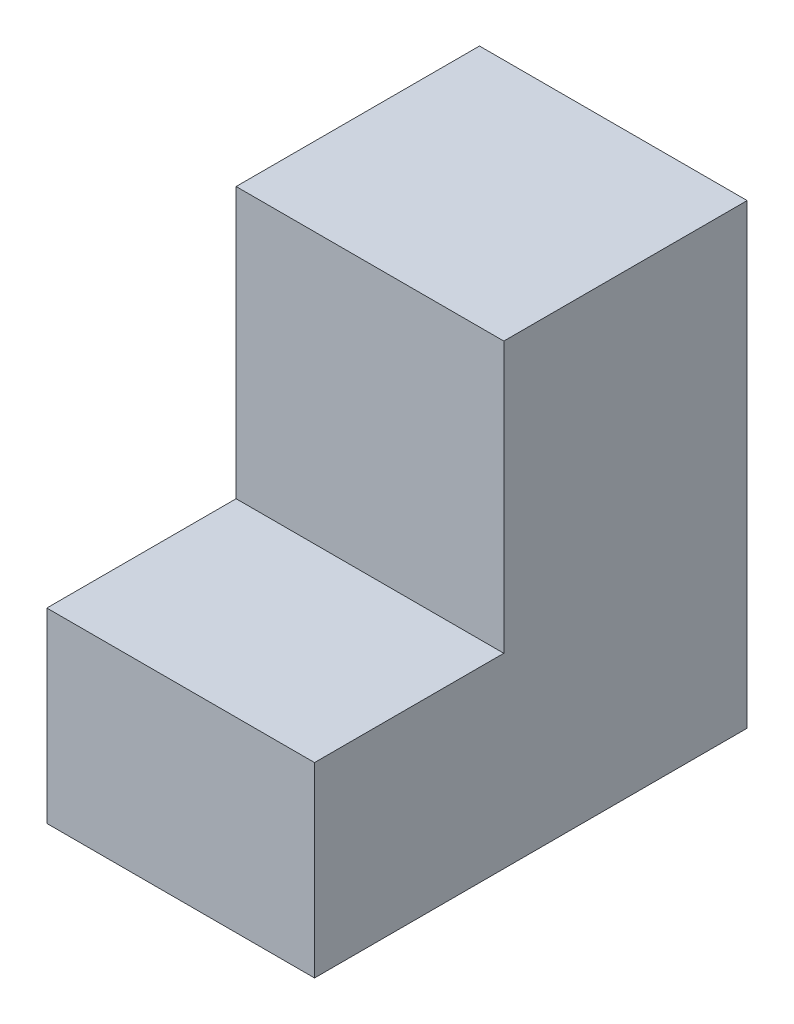
SolidWorks part; units mm, degrees
ref_plane "Front Plane" through (0, 0, 0) normal (0, 0, 1) x (1, 0, 0)
ref_plane "Top Plane" through (0, 0, 0) normal (0, 1, 0) x (1, 0, 0)
ref_plane "Right Plane" through (0, 0, 0) normal (1, 0, 0) x (0, 0, -1)
sketch "Sketch1" plane through (0, 0, 0) normal (0, 0, 1) x (1, 0, 0)
  line L1 (-4.95, -3.45) -> (4.95, -3.45)
  line L2 (-4.95, -3.45) -> (-4.95, 3.45)
  line L3 (-4.95, 3.45) -> (4.95, 3.45)
  line L4 (4.95, -3.45) -> (4.95, 3.45)
  line L5 (-4.95, -3.45) -> (4.95, 3.45) construction
  line L6 (-4.95, 3.45) -> (4.95, -3.45) construction
  point P0 (0, 0)
  dimension "D1" = 6.9
  dimension "D2" = 9.9
extrude "Boss-Extrude1" add sketch "Sketch1" along normal blind 16
sketch "Sketch2" plane through (0, 3.45, 0) normal (0, 1, 0) x (1, 0, 0)
  line L0 (4.95, 0) -> (-4.95, 0)
  line L2 (-4.95, 0) -> (-4.95, -9)
  line L3 (-4.95, -16) -> (-4.95, 0) construction
  line L4 (-4.95, -9) -> (4.95, -9)
  line L5 (4.95, -16) -> (4.95, 0) construction
  line L6 (4.95, -9) -> (4.95, 0)
  point P4 (0, 0)
  dimension "D1" = 9
extrude "Boss-Extrude2" add sketch "Sketch2" along normal blind 10
sketch "Sketch3" plane through (0, 0, 0) normal (0, 0, -1) x (-1, 0, 0)
  line L0 (0, 3.45) -> (0, -3.45) construction
  line L1 (-4.95, 3.45) -> (4.95, 3.45) construction
  line L2 (4.95, -3.45) -> (-4.95, -3.45) construction
  circle A0 centre (0, 0) radius 1.5
  dimension "D1" = 3
extrude "Boss-Extrude3" add sketch "Sketch3" along normal blind 3
